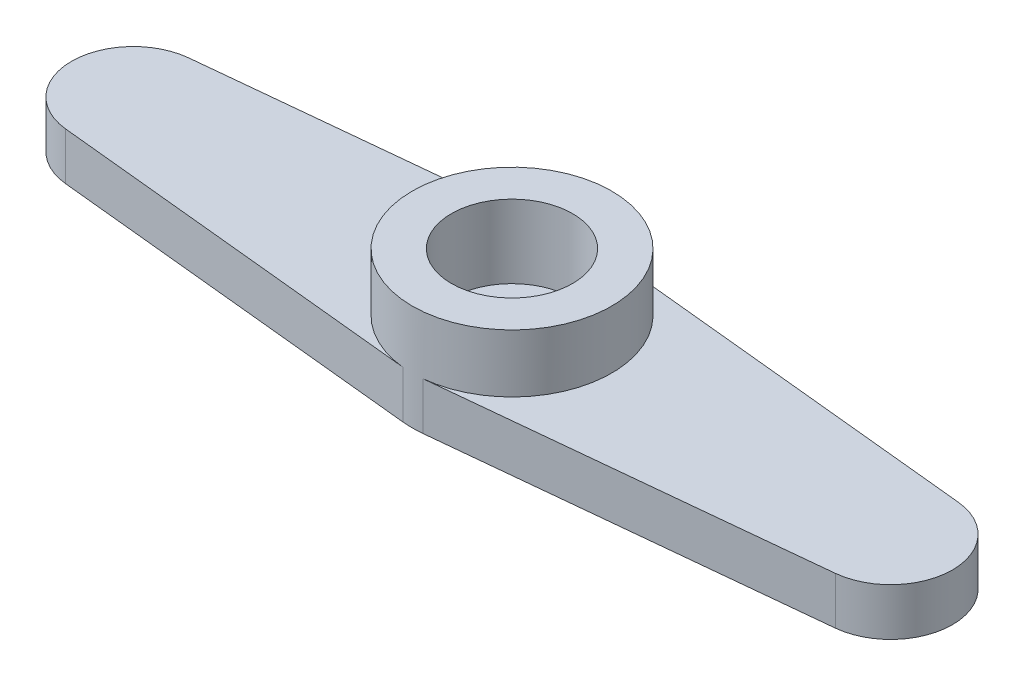
SolidWorks part; units mm, degrees
ref_plane "Plan de face" through (0, 0, 0) normal (0, 0, 1) x (1, 0, 0)
ref_plane "Plan de dessus" through (0, 0, 0) normal (0, 1, 0) x (1, 0, 0)
ref_plane "Plan de droite" through (0, 0, 0) normal (1, 0, 0) x (0, 0, -1)
sketch "Esquisse1" plane through (0, 0, 0) normal (0, 1, 0) x (1, 0, 0)
  line L0 (-0.395, 3.9302) -> (-15.245, 2.4377)
  line L1 (-0.395, -3.9302) -> (-15.245, -2.4377)
  line L2 (0.395, 3.9302) -> (15.245, 2.4377)
  line L3 (0.395, -3.9302) -> (15.245, -2.4377)
  arc A0 (-0.395, -3.9302) -> (0.395, -3.9302) centre (0, 0) ccw
  arc A1 (15.245, -2.4377) -> (15.245, 2.4377) centre (15, 0) ccw
  arc A2 (-15.245, 2.4377) -> (-15.245, -2.4377) centre (-15, 0) ccw
  arc A3 (0.395, 3.9302) -> (-0.395, 3.9302) centre (0, 0) ccw
  dimension "D1" = 7.9
  dimension "D2" = 4.9
  dimension "D3" = 4.9
  dimension "D4" = 30
  dimension "D5" = 15
extrude "Boss.-Extru.1" add sketch "Esquisse1" along normal blind 1.88
sketch "Esquisse2" plane through (0, 1.88, 0) normal (0, 1, 0) x (1, 0, 0)
  circle A0 centre (0, 0) radius 3.95
  dimension "D1" = 7.9
extrude "Boss.-Extru.2" add sketch "Esquisse2" along normal blind 2.3
sketch "Esquisse3" plane through (0, 4.18, 0) normal (0, 1, 0) x (1, 0, 0)
  circle A0 centre (0, 0) radius 2.4
  dimension "D1" = 4.8
extrude "Enlèv. mat.-Extru.1" cut sketch "Esquisse3" against normal blind 2.9
sketch "Esquisse4" plane through (0, 1.28, 0) normal (0, 1, 0) x (1, 0, 0)
  circle A0 centre (0, 0) radius 1
  dimension "D1" = 2
extrude "Enlèv. mat.-Extru.2" cut sketch "Esquisse4" against normal blind 2.9
